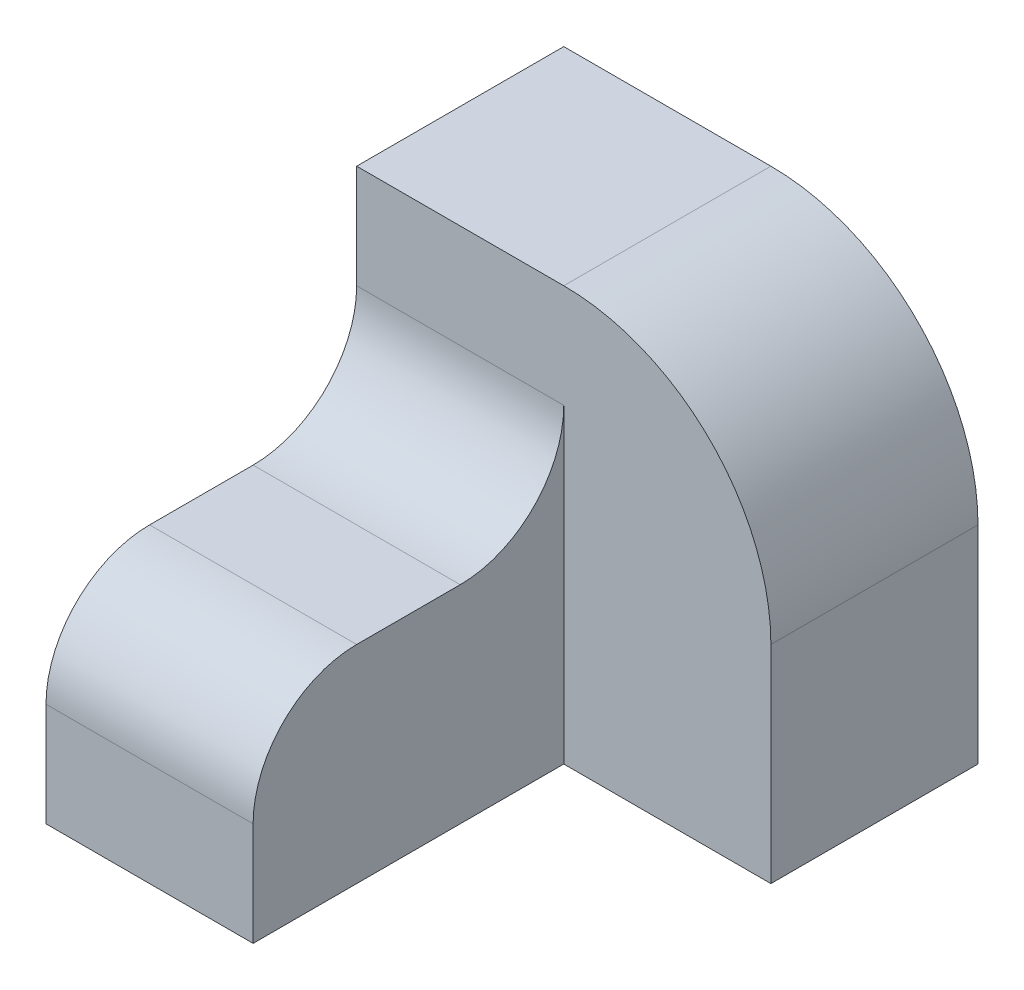
SolidWorks part; units mm, degrees
ref_plane "Front Plane" through (0, 0, 0) normal (0, 0, 1) x (1, 0, 0)
ref_plane "Top Plane" through (0, 0, 0) normal (0, 1, 0) x (1, 0, 0)
ref_plane "Right Plane" through (0, 0, 0) normal (1, 0, 0) x (0, 0, -1)
sketch "Sketch1" plane through (0, 0, 0) normal (1, 0, 0) x (0, 0, -1)
  line L0 (-10, -20) -> (-40, -20)
  line L1 (-10, 20) -> (10, 20)
  line L2 (-10, 20) -> (-10, 10)
  line L3 (-10, -20) -> (10, -20)
  line L4 (10, 20) -> (10, -20)
  line L5 (-10, 20) -> (10, -20) construction
  line L6 (-10, -20) -> (10, 20) construction
  line L7 (-40, -20) -> (-40, -10)
  line L8 (-30, 0) -> (-20, 0)
  arc A0 (-10, 10) -> (-20, 0) centre (-20, 10) cw
  arc A1 (-30, 0) -> (-40, -10) centre (-30, -10) ccw
  point P0 (0, 0)
  point P13 (-40, 0)
  dimension "D1" = 10
  dimension "D2" = 40
  dimension "D4" = 20
extrude "Boss-Extrude1" add sketch "Sketch1" along normal blind 20
sketch "Sketch2" plane through (0, 0, -10) normal (0, 0, -1) x (-1, 0, 0)
  line L1 (-40, 0) -> (-40, -20)
  line L2 (-40, -20) -> (-20, -20)
  line L3 (-20, -20) -> (-20, 20)
  arc A1 (-40, 0) -> (-20, 20) centre (-20, 0) cw
  point P8 (-40, 20)
  dimension "D2" = 20
  dimension "D1" = 20
extrude "Boss-Extrude2" add sketch "Sketch2" against normal blind 20
